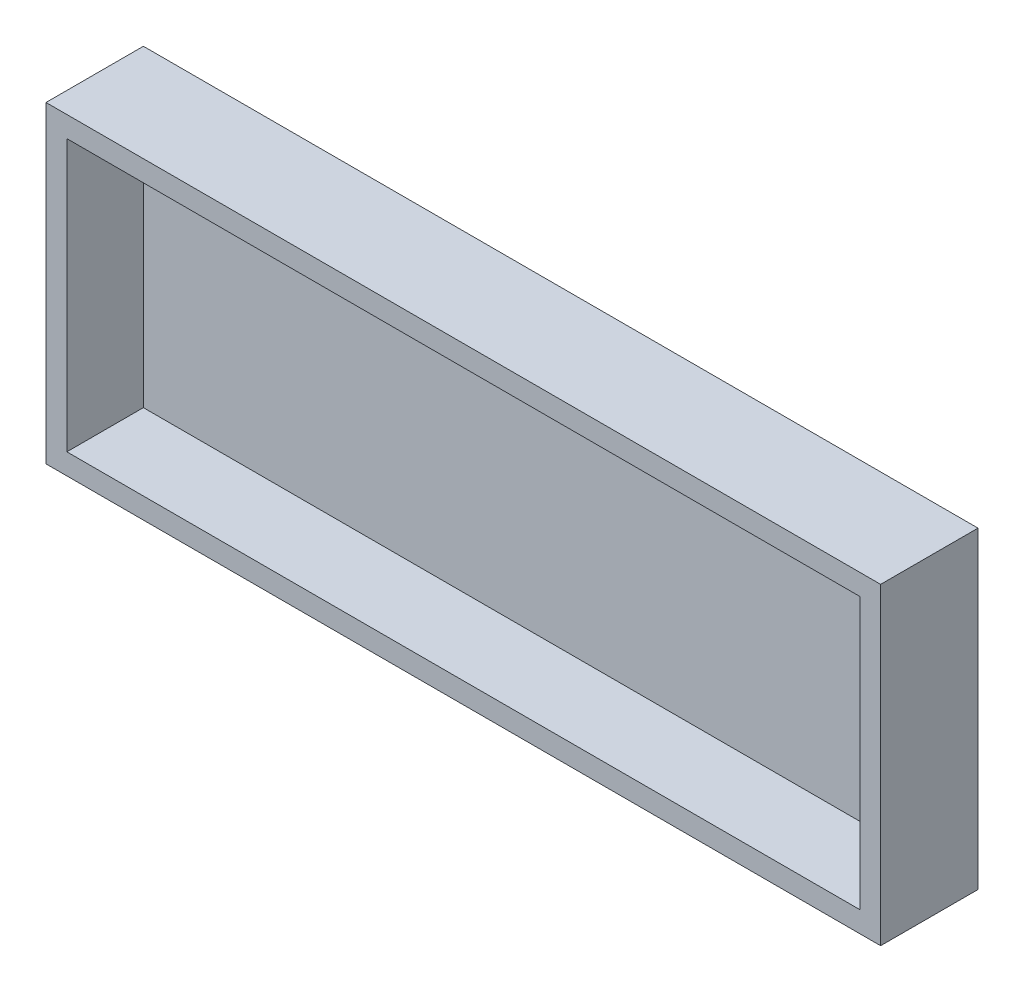
SolidWorks part; units mm, degrees
ref_plane "Front Plane" through (0, 0, 0) normal (0, 0, 1) x (1, 0, 0)
ref_plane "Top Plane" through (0, 0, 0) normal (0, 1, 0) x (1, 0, 0)
ref_plane "Right Plane" through (0, 0, 0) normal (1, 0, 0) x (0, 0, -1)
sketch "Sketch2" plane through (0, 0, 0) normal (0, 0, 1) x (1, 0, 0)
  line L1 (-60, 22.5) -> (60, 22.5)
  line L2 (-60, 22.5) -> (-60, -22.5)
  line L3 (-60, -22.5) -> (60, -22.5)
  line L4 (60, 22.5) -> (60, -22.5)
  line L5 (-60, 22.5) -> (60, -22.5) construction
  line L6 (-60, -22.5) -> (60, 22.5) construction
  point P0 (0, 0)
  dimension "D1" = 120
  dimension "D2" = 45
extrude "Boss-Extrude2" add sketch "Sketch2" along normal blind 14
shell "Shell1" thickness 3
